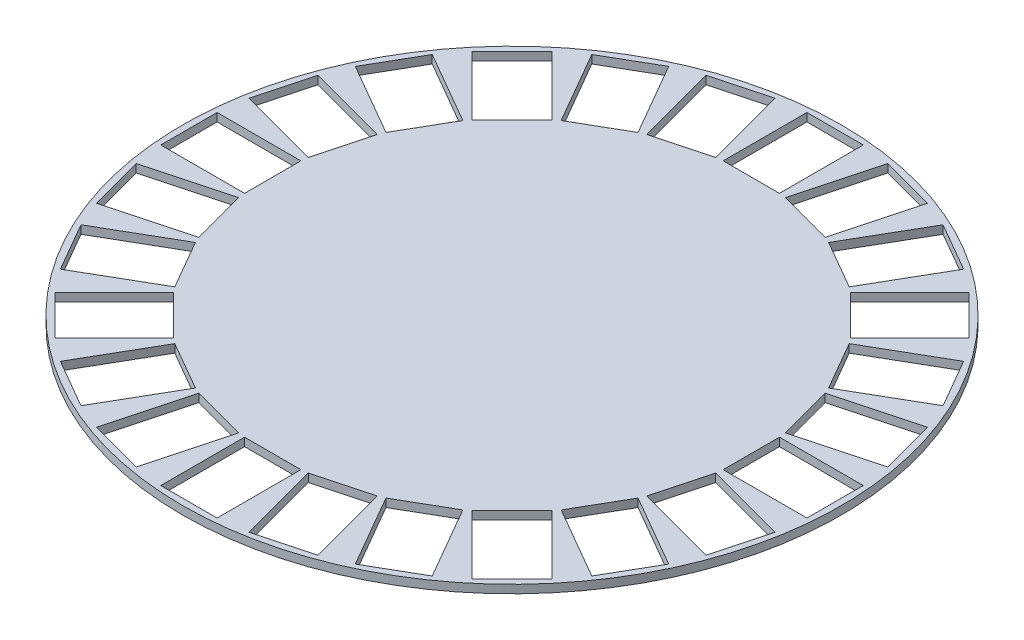
SolidWorks part; units mm, degrees
ref_plane "Front Plane" through (0, 0, 0) normal (0, 0, 1) x (1, 0, 0)
ref_plane "Top Plane" through (0, 0, 0) normal (0, 1, 0) x (1, 0, 0)
ref_plane "Right Plane" through (0, 0, 0) normal (1, 0, 0) x (0, 0, -1)
sketch "Sketch1" plane through (0, 0, 0) normal (0, 1, 0) x (1, 0, 0)
  line L0 (13.9624, -56.2789) -> (-5.914, -58.8957) construction
  line L1 (113.346, 43.1948) -> (14.2015, 56.2475) construction
  line L2 (-36.8008, 0) -> (-21.3612, 0) construction
  line L3 (0, 32.128) -> (0, 12.986) construction
  line L6 (-4.9791, 63.8158) -> (118.9515, 47.5) construction
  line L7 (-4.9791, 63.8158) -> (-5.2391, 63.85)
  line L8 (118.9515, 47.5) -> (9.893, 61.8578) construction
  line L9 (9.6329, -61.8921) -> (118.6849, -47.5351) construction
  line L10 (-4.9791, -63.8158) -> (-3.1376, -63.5733) construction
  line L11 (-4.9791, -63.8158) -> (-5.2391, -63.85) construction
  line L18 (-20.3346, 15.6631) -> (0, 12.986)
  line L22 (-20.3346, -15.6631) -> (0, -12.986)
  line L23 (-20.3346, 15.6631) -> (0, 12.986)
  line L24 (-12.2267, 45.922) -> (24.7284, 30.6147) construction
  line L25 (-12.2267, 45.922) -> (24.7284, 30.6147) construction
  line L26 (3.4364, 73.0514) -> (35.1705, 48.7009)
  line L27 (3.4364, 73.0514) -> (35.1705, 48.7009)
  line L28 (25.5874, 95.2024) -> (49.9379, 63.4683) construction
  line L29 (25.5874, 95.2024) -> (49.9379, 63.4683) construction
  line L30 (52.7168, 110.8655) -> (68.0241, 73.9104) construction
  line L31 (52.7168, 110.8655) -> (68.0241, 73.9104) construction
  line L32 (82.9757, 118.9734) -> (88.1967, 79.3156) construction
  line L33 (82.9757, 118.9734) -> (88.1967, 79.3156) construction
  line L34 (114.3019, 118.9734) -> (109.0809, 79.3156) construction
  line L35 (114.3019, 118.9734) -> (109.0809, 79.3156) construction
  line L36 (144.5608, 110.8655) -> (129.2535, 73.9104) construction
  line L37 (144.5608, 110.8655) -> (129.2535, 73.9104) construction
  line L38 (171.6902, 95.2024) -> (147.3397, 63.4683) construction
  line L39 (171.6902, 95.2024) -> (147.3397, 63.4683) construction
  line L40 (193.8412, 73.0514) -> (162.1071, 48.7009) construction
  line L41 (193.8412, 73.0514) -> (162.1071, 48.7009) construction
  line L42 (209.5043, 45.922) -> (172.5492, 30.6147) construction
  line L43 (209.5043, 45.922) -> (172.5492, 30.6147) construction
  line L44 (217.6122, 15.6631) -> (177.9544, 10.4421) construction
  line L45 (217.6122, 15.6631) -> (177.9544, 10.4421) construction
  line L46 (217.6122, -15.6631) -> (177.9544, -10.4421) construction
  line L47 (217.6122, -15.6631) -> (177.9544, -10.4421) construction
  line L48 (209.5043, -45.922) -> (172.5492, -30.6147) construction
  line L49 (209.5043, -45.922) -> (172.5492, -30.6147) construction
  line L50 (193.8412, -73.0514) -> (162.1071, -48.7009) construction
  line L51 (193.8412, -73.0514) -> (162.1071, -48.7009) construction
  line L52 (171.6902, -95.2024) -> (147.3397, -63.4683) construction
  line L53 (171.6902, -95.2024) -> (147.3397, -63.4683) construction
  line L54 (144.5608, -110.8655) -> (129.2535, -73.9104) construction
  line L55 (144.5608, -110.8655) -> (129.2535, -73.9104) construction
  line L56 (114.3019, -118.9734) -> (109.0809, -79.3156) construction
  line L57 (114.3019, -118.9734) -> (109.0809, -79.3156) construction
  line L58 (82.9757, -118.9734) -> (88.1967, -79.3156) construction
  line L59 (82.9757, -118.9734) -> (88.1967, -79.3156) construction
  line L60 (52.7168, -110.8655) -> (68.0241, -73.9104) construction
  line L61 (52.7168, -110.8655) -> (68.0241, -73.9104) construction
  line L62 (25.5874, -95.2024) -> (49.9379, -63.4683) construction
  line L63 (25.5874, -95.2024) -> (49.9379, -63.4683) construction
  line L64 (19.7081, -60.5656) -> (35.1705, -48.7009)
  line L65 (19.7081, -60.5656) -> (35.1705, -48.7009)
  line L66 (-12.2267, -45.922) -> (24.7284, -30.6147) construction
  line L67 (-12.2267, -45.922) -> (24.7284, -30.6147) construction
  line L68 (-20.3346, -15.6631) -> (0, -12.986)
  line L69 (0, 12.986) -> (19.3232, 10.4421) construction
  line L70 (0, 12.986) -> (19.3232, 10.4421) construction
  line L71 (0, 12.986) -> (0, 0) construction
  line L72 (0, -12.986) -> (0, -36.1975) construction
  line L73 (-21.3612, 0) -> (0, 0) construction
  line L74 (0, 0) -> (38.6388, 0) construction
  line L75 (0, 0) -> (0, -12.986) construction
  line L76 (0, -12.986) -> (19.3232, -10.4421) construction
  line L77 (0, -12.986) -> (19.3232, -10.4421) construction
  line L78 (-5.914, -58.8957) -> (38.73, -53.0182) construction
  line L79 (38.73, -53.0182) -> (113.1069, -43.2263) construction
  line L80 (13.9624, -56.2789) -> (113.1069, -43.2263) construction
  line L81 (-3.1376, -63.5733) -> (19.7081, -60.5656) construction
  line L82 (19.7081, -60.5656) -> (118.6849, -47.5351) construction
  line L83 (3.4364, -73.0514) -> (19.7081, -60.5656) construction
  line L84 (3.4364, -73.0514) -> (19.7081, -60.5656) construction
  arc A0 (14.2015, 56.2475) -> (13.9624, -56.2789) centre (470.8487, -0.9863) ccw construction
  arc A1 (113.346, 43.1948) -> (113.1069, -43.2263) centre (470.697, -1.0048) ccw construction
  arc A2 (118.9515, 47.5) -> (118.6849, -47.5351) centre (470.697, -1.0048) ccw construction
  arc A4 (-5.2391, -63.85) -> (-4.9791, 63.8158) centre (470.8487, -0.9863) cw construction
  arc A5 (9.893, 61.8578) -> (9.6329, -61.8921) centre (470.8487, -0.9863) ccw construction
  arc A8 (-20.3346, -15.6631) -> (-20.3346, 15.6631) centre (98.6388, 0) cw
  arc A9 (19.3232, 10.4421) -> (18.6779, 2.5) centre (98.6388, 0) ccw
  arc A10 (24.7284, 30.6147) -> (19.3232, 10.4421) centre (98.6388, 0) ccw
  arc A11 (-20.3346, 15.6631) -> (-12.2267, 45.922) centre (98.6388, 0) cw
  arc A12 (35.1705, 48.7009) -> (24.7284, 30.6147) centre (98.6388, 0) ccw
  arc A13 (-12.2267, 45.922) -> (3.4364, 73.0514) centre (98.6388, 0) cw
  arc A14 (49.9379, 63.4683) -> (35.1705, 48.7009) centre (98.6388, 0) ccw
  arc A15 (3.4364, 73.0514) -> (25.5874, 95.2024) centre (98.6388, 0) cw
  arc A16 (68.0241, 73.9104) -> (49.9379, 63.4683) centre (98.6388, 0) ccw
  arc A17 (25.5874, 95.2024) -> (52.7168, 110.8655) centre (98.6388, 0) cw
  arc A18 (88.1967, 79.3156) -> (68.0241, 73.9104) centre (98.6388, 0) ccw
  arc A19 (52.7168, 110.8655) -> (82.9757, 118.9734) centre (98.6388, 0) cw
  arc A20 (109.0809, 79.3156) -> (88.1967, 79.3156) centre (98.6388, 0) ccw
  arc A21 (82.9757, 118.9734) -> (114.3019, 118.9734) centre (98.6388, 0) cw
  arc A22 (129.2535, 73.9104) -> (109.0809, 79.3156) centre (98.6388, 0) ccw
  arc A23 (114.3019, 118.9734) -> (144.5608, 110.8655) centre (98.6388, 0) cw
  arc A24 (147.3397, 63.4683) -> (129.2535, 73.9104) centre (98.6388, 0) ccw
  arc A25 (144.5608, 110.8655) -> (171.6902, 95.2024) centre (98.6388, 0) cw
  arc A26 (162.1071, 48.7009) -> (147.3397, 63.4683) centre (98.6388, 0) ccw
  arc A27 (171.6902, 95.2024) -> (193.8412, 73.0514) centre (98.6388, 0) cw
  arc A28 (172.5492, 30.6147) -> (162.1071, 48.7009) centre (98.6388, 0) ccw
  arc A29 (193.8412, 73.0514) -> (209.5043, 45.922) centre (98.6388, 0) cw
  arc A30 (177.9544, 10.4421) -> (172.5492, 30.6147) centre (98.6388, 0) ccw
  arc A31 (209.5043, 45.922) -> (217.6122, 15.6631) centre (98.6388, 0) cw
  arc A32 (177.9544, -10.4421) -> (177.9544, 10.4421) centre (98.6388, 0) ccw
  arc A33 (217.6122, 15.6631) -> (217.6122, -15.6631) centre (98.6388, 0) cw
  arc A34 (172.5492, -30.6147) -> (177.9544, -10.4421) centre (98.6388, 0) ccw
  arc A35 (217.6122, -15.6631) -> (209.5043, -45.922) centre (98.6388, 0) cw
  arc A36 (162.1071, -48.7009) -> (172.5492, -30.6147) centre (98.6388, 0) ccw
  arc A37 (209.5043, -45.922) -> (193.8412, -73.0514) centre (98.6388, 0) cw
  arc A38 (147.3397, -63.4683) -> (162.1071, -48.7009) centre (98.6388, 0) ccw
  arc A39 (193.8412, -73.0514) -> (171.6902, -95.2024) centre (98.6388, 0) cw
  arc A40 (129.2535, -73.9104) -> (147.3397, -63.4683) centre (98.6388, 0) ccw
  arc A41 (171.6902, -95.2024) -> (144.5608, -110.8655) centre (98.6388, 0) cw
  arc A42 (109.0809, -79.3156) -> (129.2535, -73.9104) centre (98.6388, 0) ccw
  arc A43 (144.5608, -110.8655) -> (114.3019, -118.9734) centre (98.6388, 0) cw
  arc A44 (88.1967, -79.3156) -> (109.0809, -79.3156) centre (98.6388, 0) ccw
  arc A45 (114.3019, -118.9734) -> (82.9757, -118.9734) centre (98.6388, 0) cw
  arc A46 (68.0241, -73.9104) -> (88.1967, -79.3156) centre (98.6388, 0) ccw
  arc A47 (82.9757, -118.9734) -> (52.7168, -110.8655) centre (98.6388, 0) cw
  arc A48 (49.9379, -63.4683) -> (68.0241, -73.9104) centre (98.6388, 0) ccw
  arc A49 (52.7168, -110.8655) -> (25.5874, -95.2024) centre (98.6388, 0) cw
  arc A50 (35.1705, -48.7009) -> (49.9379, -63.4683) centre (98.6388, 0) ccw
  arc A51 (25.5874, -95.2024) -> (3.4364, -73.0514) centre (98.6388, 0) cw
  arc A52 (24.7284, -30.6147) -> (35.1705, -48.7009) centre (98.6388, 0) ccw
  arc A53 (3.4364, -73.0514) -> (-12.2267, -45.922) centre (98.6388, 0) cw
  arc A54 (19.3232, -10.4421) -> (24.7284, -30.6147) centre (98.6388, 0) ccw
  arc A55 (-12.2267, -45.922) -> (-20.3346, -15.6631) centre (98.6388, 0) cw
  arc A56 (18.6779, 2.5) -> (18.6388, 0) centre (98.6388, 0) ccw
  arc A57 (18.6779, -2.5) -> (19.3232, -10.4421) centre (98.6388, 0) ccw
  arc A58 (18.6388, 0) -> (18.6779, -2.5) centre (98.6388, 0) ccw
  circle A59 centre (98.6388, 0) radius 80
  point P21 (0, 0)
  point P123 (98.6388, 0)
  dimension "D1" = 47.5
  dimension "D2" = 63.85
  dimension "D4" = 100
  dimension "D8" = 125
  dimension "D10" = 80
  dimension "D11" = 120
  dimension "D3" = 7.5
  dimension "D5" = 100
  dimension "D7" = 40
  dimension "D9" = 24
  dimension "D12" = 7.5
  dimension "D6" = 5
extrude "Boss-Extrude1" add sketch "Sketch1" along normal mid plane 3
sketch "Sketch6" plane through (0, 1.5, 0) normal (0, 1, 0) x (1, 0, 0)
  line L0 (18.6388, 0) -> (0, 0) construction
  line L1 (-19, 10.25) -> (11.5, 10.25)
  line L2 (-19, 10.25) -> (-19, -10.25)
  line L3 (-19, -10.25) -> (11.5, -10.25)
  line L4 (11.5, 10.25) -> (11.5, -10.25)
  line L5 (-19, 10.25) -> (11.5, -10.25) construction
  line L6 (-19, -10.25) -> (11.5, 10.25) construction
  line L7 (-12.3387, 40.3479) -> (-17.6445, 20.5464)
  line L8 (-12.3387, 40.3479) -> (17.1221, 32.4539)
  line L9 (17.1221, 32.4539) -> (11.8163, 12.6524)
  line L10 (-17.6445, 20.5464) -> (11.8163, 12.6524)
  line L11 (1.8856, 67.6962) -> (-8.3644, 49.9426)
  line L12 (1.8856, 67.6962) -> (28.2994, 52.4462)
  line L13 (28.2994, 52.4462) -> (18.0494, 34.6926)
  line L14 (-8.3644, 49.9426) -> (18.0494, 34.6926)
  line L15 (22.7035, 90.431) -> (8.2078, 75.9353)
  line L16 (22.7035, 90.431) -> (44.2702, 68.8643)
  line L17 (44.2702, 68.8643) -> (29.7745, 54.3686)
  line L18 (8.2078, 75.9353) -> (29.7745, 54.3686)
  line L19 (48.6962, 107.0032) -> (30.9426, 96.7532)
  line L20 (48.6962, 107.0032) -> (63.9462, 80.5894)
  line L21 (63.9462, 80.5894) -> (46.1926, 70.3394)
  line L22 (30.9426, 96.7532) -> (46.1926, 70.3394)
  line L23 (78.0924, 116.2832) -> (58.2909, 110.9775)
  line L24 (78.0924, 116.2832) -> (85.9864, 86.8225)
  line L25 (85.9864, 86.8225) -> (66.1849, 81.5167)
  line L26 (58.2909, 110.9775) -> (66.1849, 81.5167)
  line L27 (108.8888, 117.6388) -> (88.3888, 117.6388)
  line L28 (108.8888, 117.6388) -> (108.8888, 87.1388)
  line L29 (108.8888, 87.1388) -> (88.3888, 87.1388)
  line L30 (88.3888, 117.6388) -> (88.3888, 87.1388)
  line L31 (138.9867, 110.9775) -> (119.1852, 116.2832)
  line L32 (138.9867, 110.9775) -> (131.0927, 81.5167)
  line L33 (131.0927, 81.5167) -> (111.2912, 86.8225)
  line L34 (119.1852, 116.2832) -> (111.2912, 86.8225)
  line L35 (166.335, 96.7532) -> (148.5814, 107.0032)
  line L36 (166.335, 96.7532) -> (151.085, 70.3394)
  line L37 (151.085, 70.3394) -> (133.3314, 80.5894)
  line L38 (148.5814, 107.0032) -> (133.3314, 80.5894)
  line L39 (189.0698, 75.9353) -> (174.5741, 90.431)
  line L40 (189.0698, 75.9353) -> (167.5031, 54.3686)
  line L41 (167.5031, 54.3686) -> (153.0074, 68.8643)
  line L42 (174.5741, 90.431) -> (153.0074, 68.8643)
  line L43 (205.642, 49.9426) -> (195.392, 67.6962)
  line L44 (205.642, 49.9426) -> (179.2282, 34.6926)
  line L45 (179.2282, 34.6926) -> (168.9782, 52.4462)
  line L46 (195.392, 67.6962) -> (168.9782, 52.4462)
  line L47 (214.922, 20.5464) -> (209.6163, 40.3479)
  line L48 (214.922, 20.5464) -> (185.4613, 12.6524)
  line L49 (185.4613, 12.6524) -> (180.1555, 32.4539)
  line L50 (209.6163, 40.3479) -> (180.1555, 32.4539)
  line L51 (216.2776, -10.25) -> (216.2776, 10.25)
  line L52 (216.2776, -10.25) -> (185.7776, -10.25)
  line L53 (185.7776, -10.25) -> (185.7776, 10.25)
  line L54 (216.2776, 10.25) -> (185.7776, 10.25)
  line L55 (209.6163, -40.3479) -> (214.922, -20.5464)
  line L56 (209.6163, -40.3479) -> (180.1555, -32.4539)
  line L57 (180.1555, -32.4539) -> (185.4613, -12.6524)
  line L58 (214.922, -20.5464) -> (185.4613, -12.6524)
  line L59 (195.392, -67.6962) -> (205.642, -49.9426)
  line L60 (195.392, -67.6962) -> (168.9782, -52.4462)
  line L61 (168.9782, -52.4462) -> (179.2282, -34.6926)
  line L62 (205.642, -49.9426) -> (179.2282, -34.6926)
  line L63 (174.5741, -90.431) -> (189.0698, -75.9353)
  line L64 (174.5741, -90.431) -> (153.0074, -68.8643)
  line L65 (153.0074, -68.8643) -> (167.5031, -54.3686)
  line L66 (189.0698, -75.9353) -> (167.5031, -54.3686)
  line L67 (148.5814, -107.0032) -> (166.335, -96.7532)
  line L68 (148.5814, -107.0032) -> (133.3314, -80.5894)
  line L69 (133.3314, -80.5894) -> (151.085, -70.3394)
  line L70 (166.335, -96.7532) -> (151.085, -70.3394)
  line L71 (119.1852, -116.2832) -> (138.9867, -110.9775)
  line L72 (119.1852, -116.2832) -> (111.2912, -86.8225)
  line L73 (111.2912, -86.8225) -> (131.0927, -81.5167)
  line L74 (138.9867, -110.9775) -> (131.0927, -81.5167)
  line L75 (88.3888, -117.6388) -> (108.8888, -117.6388)
  line L76 (88.3888, -117.6388) -> (88.3888, -87.1388)
  line L77 (88.3888, -87.1388) -> (108.8888, -87.1388)
  line L78 (108.8888, -117.6388) -> (108.8888, -87.1388)
  line L79 (58.2909, -110.9775) -> (78.0924, -116.2832)
  line L80 (58.2909, -110.9775) -> (66.1849, -81.5167)
  line L81 (66.1849, -81.5167) -> (85.9864, -86.8225)
  line L82 (78.0924, -116.2832) -> (85.9864, -86.8225)
  line L83 (30.9426, -96.7532) -> (48.6962, -107.0032)
  line L84 (30.9426, -96.7532) -> (46.1926, -70.3394)
  line L85 (46.1926, -70.3394) -> (63.9462, -80.5894)
  line L86 (48.6962, -107.0032) -> (63.9462, -80.5894)
  line L87 (8.2078, -75.9353) -> (22.7035, -90.431)
  line L88 (8.2078, -75.9353) -> (29.7745, -54.3686)
  line L89 (29.7745, -54.3686) -> (44.2702, -68.8643)
  line L90 (22.7035, -90.431) -> (44.2702, -68.8643)
  line L91 (-8.3644, -49.9426) -> (1.8856, -67.6962)
  line L92 (-8.3644, -49.9426) -> (18.0494, -34.6926)
  line L93 (18.0494, -34.6926) -> (28.2994, -52.4462)
  line L94 (1.8856, -67.6962) -> (28.2994, -52.4462)
  line L95 (-17.6445, -20.5464) -> (-12.3387, -40.3479)
  line L96 (-17.6445, -20.5464) -> (11.8163, -12.6524)
  line L97 (11.8163, -12.6524) -> (17.1221, -32.4539)
  line L98 (-12.3387, -40.3479) -> (17.1221, -32.4539)
  circle A0 centre (98.6388, 0) radius 80 construction
  point P0 (-3.75, 0)
  point P104 (98.6388, 0)
  dimension "D1" = 20.5
  dimension "D2" = 30.5
  dimension "D3" = 3.75
  dimension "D4" = 24
extrude "Cut-Extrude1" cut sketch "Sketch6" against normal blind 10.5
